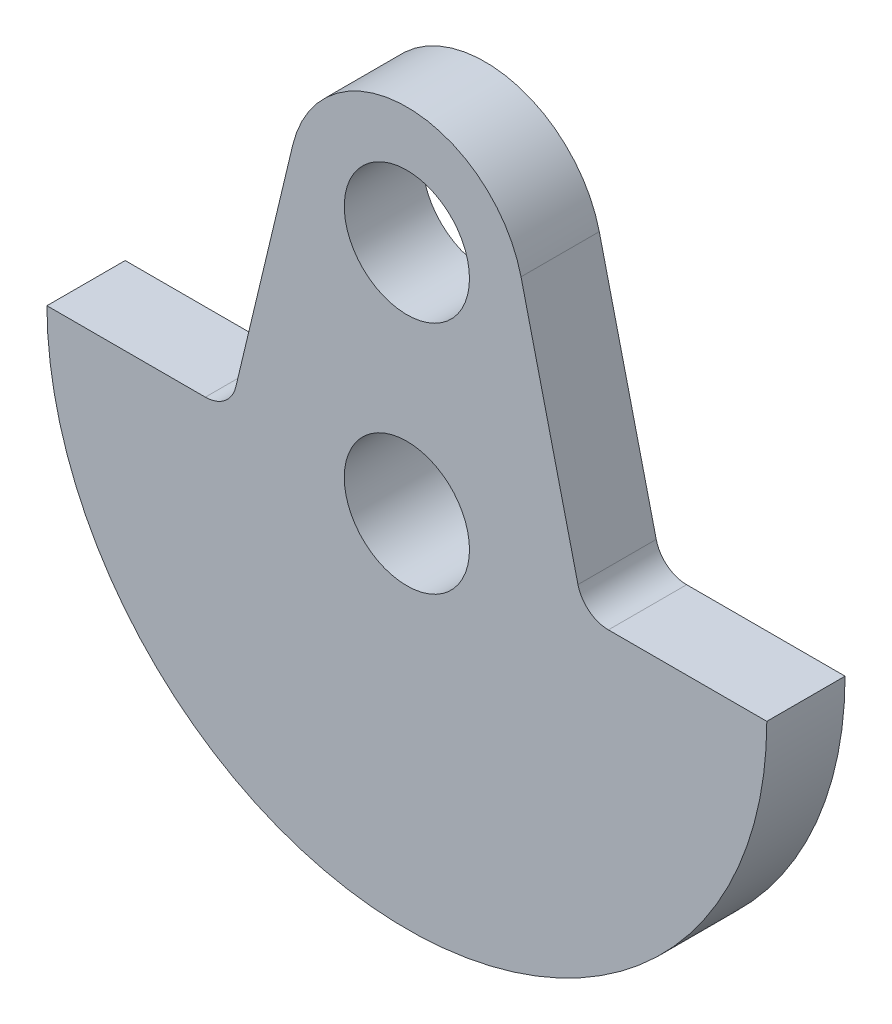
SolidWorks part; units mm, degrees
ref_plane "Front Plane" through (0, 0, 0) normal (0, 0, 1) x (1, 0, 0)
ref_plane "Top Plane" through (0, 0, 0) normal (0, 1, 0) x (1, 0, 0)
ref_plane "Right Plane" through (0, 0, 0) normal (1, 0, 0) x (0, 0, -1)
sketch "Sketch1" plane through (0, 0, 0) normal (0, 0, 1) x (1, 0, 0)
  line L0 (-23, -15) -> (-12.878, -15)
  line L1 (-10.9329, -13.4653) -> (-7.2942, 1.745)
  line L2 (0, 0) -> (0, -15.5763) construction
  line L3 (10.9329, -13.4653) -> (7.2942, 1.745)
  line L4 (12.878, -15) -> (23, -15)
  arc A0 (7.2942, 1.745) -> (-7.2942, 1.745) centre (0, 0) ccw
  circle A1 centre (0, 0) radius 4
  arc A2 (-23, -15) -> (23, -15) centre (0, -15) ccw
  arc A3 (10.9329, -13.4653) -> (12.878, -15) centre (12.878, -13) ccw
  arc A4 (-10.9329, -13.4653) -> (-12.878, -15) centre (-12.878, -13) cw
  circle A5 centre (0, -15) radius 4
  point P13 (11.3, -15)
  point P16 (-11.3, -15)
  dimension "D1" = 15
  dimension "D2" = 8
  dimension "D3" = 46
  dimension "D6" = 2
  dimension "D7" = 8
  dimension "D4" = 15
  dimension "D5" = 11.7
extrude "Boss-Extrude1" add sketch "Sketch1" along normal blind 5
sketch "Sketch3" plane through (0, 0, 0) normal (0, 0, -1) x (-1, 0, 0)
  circle A0 centre (0, -15) radius 6
  circle A1 centre (0, -15) radius 4 construction
  circle A2 centre (0, -15) radius 4
  dimension "D1" = 12
extrude "Boss-Extrude2" add sketch "Sketch3" along normal blind 1
